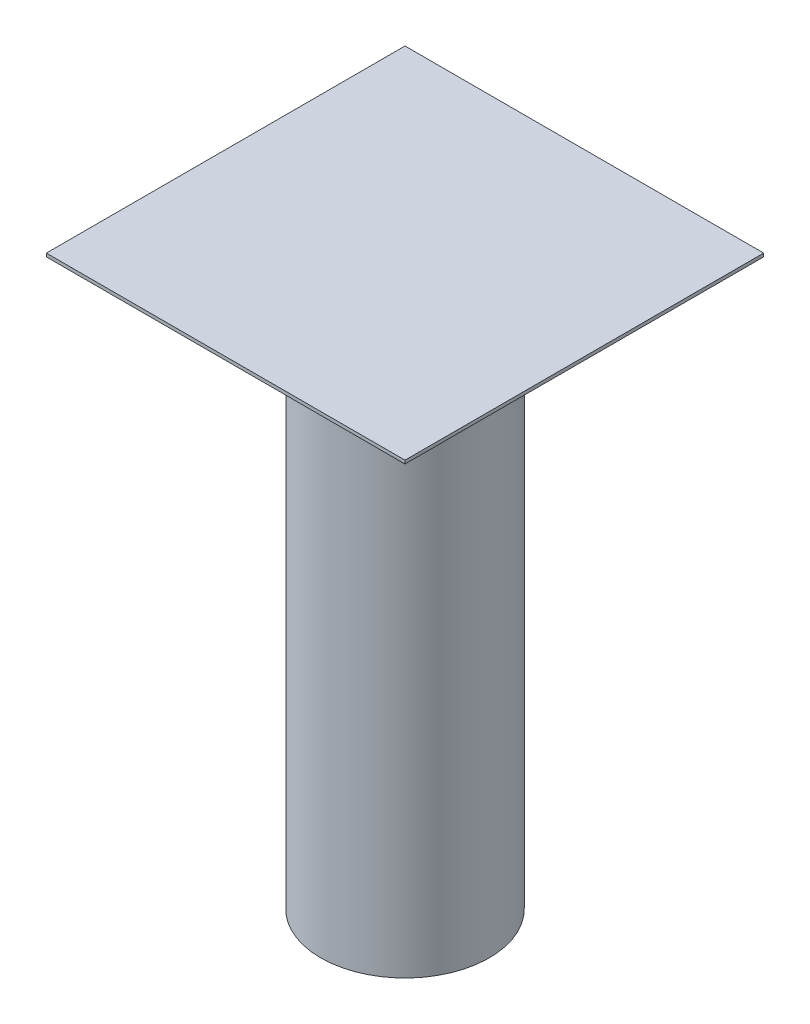
SolidWorks part; units mm, degrees
ref_plane "Front Plane" through (0, 0, 0) normal (0, 0, 1) x (1, 0, 0)
ref_plane "Top Plane" through (0, 0, 0) normal (0, 1, 0) x (1, 0, 0)
ref_plane "Right Plane" through (0, 0, 0) normal (1, 0, 0) x (0, 0, -1)
sketch "Sketch1" plane through (0, 0, 0) normal (0, 1, 0) x (1, 0, 0)
  circle A0 centre (0, 0) radius 25.4
  dimension "D1" = 50.8
extrude "Boss-Extrude1" add sketch "Sketch1" along normal blind 170.1
sketch "Sketch2" plane through (0, 170.1, 0) normal (0, 1, 0) x (1, 0, 0)
  circle A0 centre (0, 0) radius 24.65
  dimension "D1" = 49.3
extrude "Cut-Extrude1" cut sketch "Sketch2" against normal through all
sketch "Sketch3" plane through (0, 170.1, 0) normal (0, 1, 0) x (1, 0, 0)
  line L1 (-54, -54) -> (54, -54)
  line L2 (-54, -54) -> (-54, 54)
  line L3 (-54, 54) -> (54, 54)
  line L4 (54, -54) -> (54, 54)
  line L5 (-54, -54) -> (54, 54) construction
  line L6 (-54, 54) -> (54, -54) construction
  point P0 (0, 0)
  dimension "D1" = 108
  dimension "D2" = 108
extrude "Boss-Extrude2" add sketch "Sketch3" along normal blind 1
